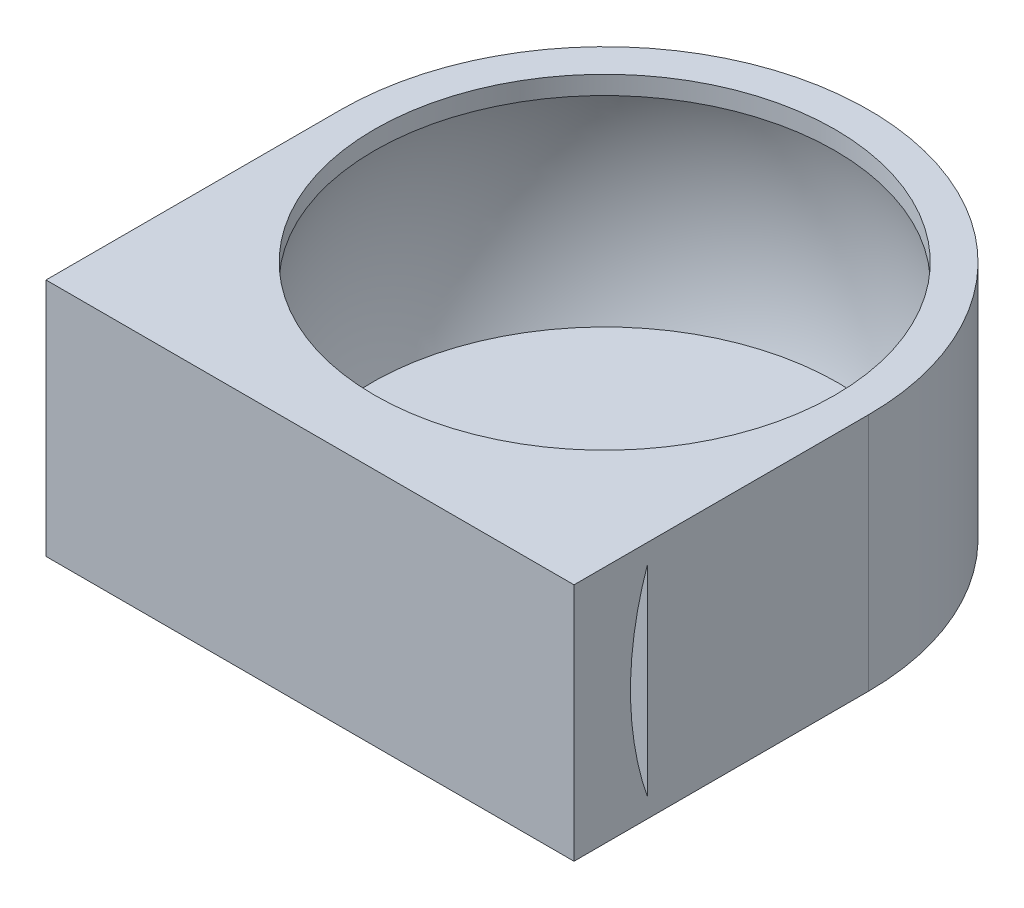
SolidWorks part; units mm, degrees
ref_plane "Front Plane" through (0, 0, 0) normal (0, 0, 1) x (1, 0, 0)
ref_plane "Top Plane" through (0, 0, 0) normal (0, 1, 0) x (1, 0, 0)
ref_plane "Right Plane" through (0, 0, 0) normal (1, 0, 0) x (0, 0, -1)
sketch "Sketch1" plane through (0, 0, 0) normal (0, 0, 1) x (1, 0, 0)
  line L1 (0, 0) -> (37, 0)
  line L2 (0, 0) -> (0, 32)
  line L3 (0, 32) -> (37, 32)
  line L4 (37, 0) -> (37, 32)
  line L5 (0, -0.5) -> (38, -0.5)
  line L6 (0, -0.5) -> (0, 32.5)
  line L7 (0, 32.5) -> (38, 32.5)
  line L8 (38, -0.5) -> (38, 32.5)
  line L9 (0, -0.5) -> (38, 32.5) construction
  line L10 (0, 32.5) -> (38, -0.5) construction
  line L11 (0, -3.5) -> (43, -3.5)
  line L12 (0, -3.5) -> (0, 35.5)
  line L13 (0, 35.5) -> (43, 35.5)
  line L14 (43, -3.5) -> (43, 35.5)
  arc A0 (38, 32.5) -> (38, -0.5) centre (-9.199, 16) cw
  point P5 (19, 16)
  dimension "D11" = 50
  dimension "D1" = 37
  dimension "D2" = 32
  dimension "D3" = 38
  dimension "D4" = 33
  dimension "D5" = 1
  dimension "D6" = 0.5
  dimension "D7" = 39
  dimension "D8" = 3
  dimension "D9" = 43
  dimension "D10" = 0
revolve "Revolve1" add sketch "Sketch1" angle 360 about L6
sketch "Sketch2" plane through (0, 35.5, 0) normal (0, 1, 0) x (1, 0, 0)
  circle A0 centre (0, 0) radius 37.5
  dimension "D1" = 75
extrude "Cut-Extrude1" cut sketch "Sketch2" against normal blind 3
sketch "Sketch3" plane through (0, 35.5, 0) normal (0, 1, 0) x (1, 0, 0)
  line L0 (-43, 0) -> (-43, -43)
  line L1 (-43, -43) -> (0, -43)
  line L2 (43, 0) -> (43, -43)
  line L3 (43, -43) -> (0, -43)
  line L5 (-43, -43) -> (43, -43)
  line L6 (-43, -43) -> (-43, -48)
  line L7 (-43, -48) -> (43, -48)
  line L8 (43, -43) -> (43, -48)
  circle A0 centre (0, 0) radius 43 construction
  circle M3 centre (0, 0) radius 43
  dimension "D1" = 5
extrude "Boss-Extrude1" add sketch "Sketch3" against normal up to surface (39 mm away) contours L0 L1 M3 | L3 L2 M3 | L8 L3 L1 L6 L7 up to face at (0, -3.5, -43)
sketch "Sketch4" plane through (43, 0, 0) normal (1, 0, 0) x (0, 0, -1)
  line L0 (0, -3.5) -> (-48, -3.5) construction
  line L1 (-48, 35.5) -> (-43, 35.5)
  line L2 (-48, 35.5) -> (-48, -3.5)
  line L3 (-48, -3.5) -> (-43, -3.5)
  line L4 (-43, 35.5) -> (-43, -3.5)
  line L5 (43, 16) -> (-36, 16)
  line L6 (43, -3.5) -> (43, 35.5) construction
  line L7 (0, 35.5) -> (-48, 35.5) construction
  line L8 (-43, 32.5) -> (-36, 32.5)
  line L9 (-43, 32.5) -> (-43, -0.5)
  line L10 (-43, -0.5) -> (-36, -0.5)
  line L11 (-36, 32.5) -> (-36, -0.5)
  arc A0 (-36, 32.5) -> (-36, -0.5) centre (11.199, 16) ccw
  dimension "D6" = 50
  dimension "D1" = 5
  dimension "D2" = 79
  dimension "D3" = 0
  dimension "D4" = 3
  dimension "D5" = 3
extrude "Cut-Extrude2" cut sketch "Sketch4" against normal blind 40 and the other way through all contours L11 A0
